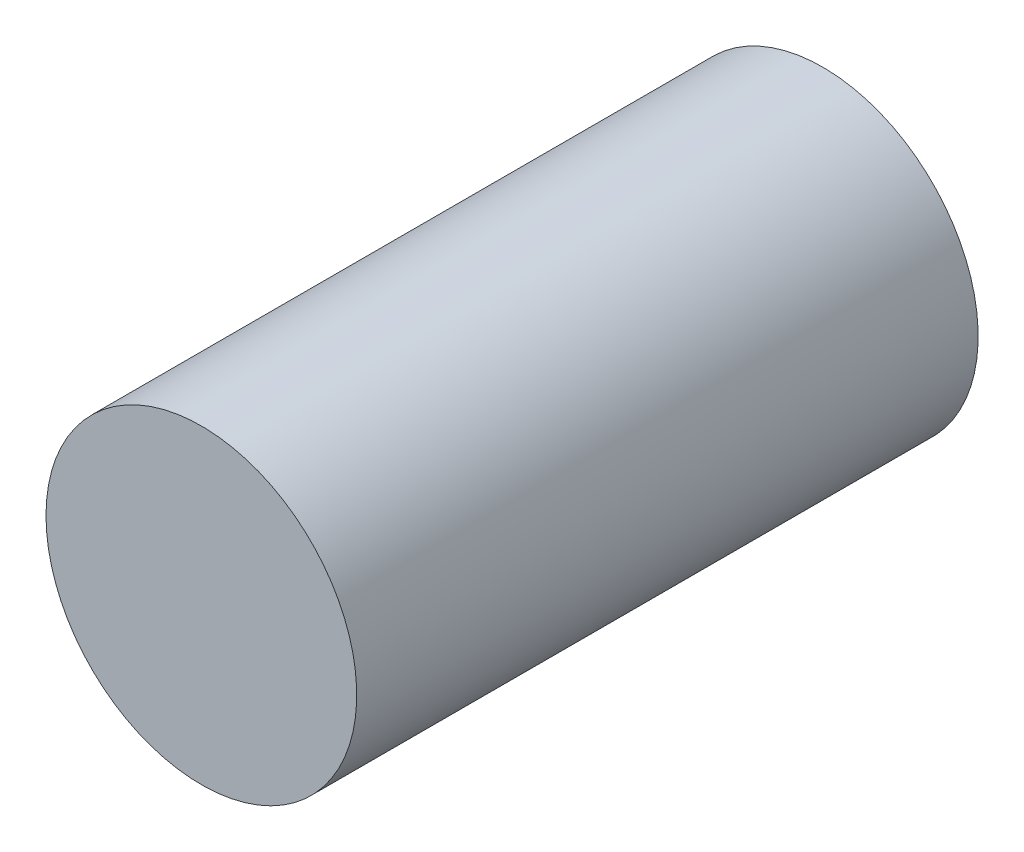
SolidWorks part; units mm, degrees
ref_plane "Front Plane" through (0, 0, 0) normal (0, 0, 1) x (1, 0, 0)
ref_plane "Top Plane" through (0, 0, 0) normal (0, 1, 0) x (1, 0, 0)
ref_plane "Right Plane" through (0, 0, 0) normal (1, 0, 0) x (0, 0, -1)
sketch "Sketch1" plane through (0, 0, 0) normal (0, 0, 1) x (1, 0, 0)
  circle A0 centre (0, 0) radius 38.1
  dimension "D1" = 76.2
extrude "Boss-Extrude1" add sketch "Sketch1" along normal blind 152.4
